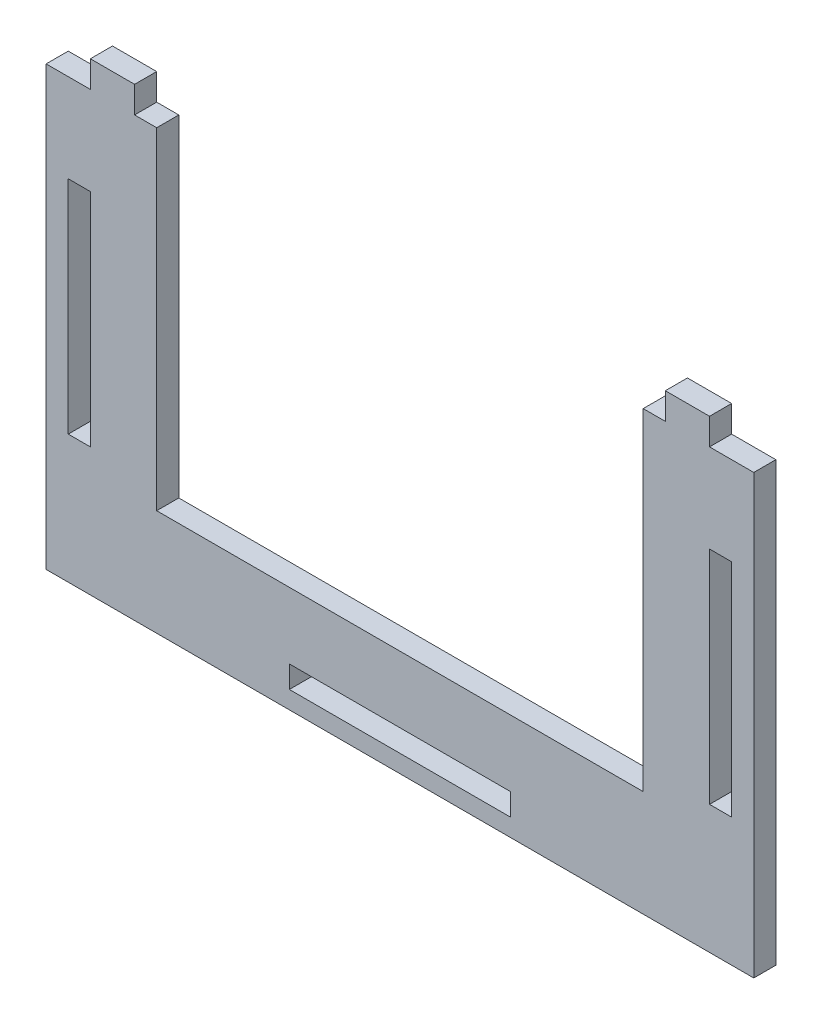
SolidWorks part; units mm, degrees
ref_plane "Front Plane" through (0, 0, 0) normal (0, 0, 1) x (1, 0, 0)
ref_plane "Top Plane" through (0, 0, 0) normal (0, 1, 0) x (1, 0, 0)
ref_plane "Right Plane" through (0, 0, 0) normal (1, 0, 0) x (0, 0, -1)
sketch "Sketch1" plane through (0, 0, 0) normal (0, 0, 1) x (1, 0, 0)
  line L0 (-44.45, 28.575) -> (-44.45, -34.29) construction
  line L1 (-50.8, 28.575) -> (-44.45, 28.575)
  line L2 (-50.8, 28.575) -> (-50.8, -34.29)
  line L3 (-50.8, -34.29) -> (50.8, -34.29)
  line L4 (50.8, 28.575) -> (50.8, -34.29)
  line L5 (44.45, 28.575) -> (44.45, -34.29) construction
  line L6 (-15.875, -28.575) -> (-50.8, -28.575) construction
  line L7 (-15.875, -28.575) -> (15.875, -28.575)
  line L8 (-15.875, -28.575) -> (-15.875, -31.75)
  line L9 (-15.875, -31.75) -> (15.875, -31.75)
  line L10 (15.875, -28.575) -> (15.875, -31.75)
  line L11 (15.875, -28.575) -> (50.8, -28.575) construction
  line L12 (34.925, 28.575) -> (38.1, 28.575)
  line L13 (0, -19.05) -> (0, 0) construction
  line L14 (-38.1, 28.575) -> (-34.925, 28.575)
  line L16 (-44.45, 28.575) -> (-44.45, 32.385)
  line L17 (-47.625, 0) -> (47.625, 0) construction
  line L18 (0, -34.29) -> (0, -31.75) construction
  line L19 (-47.625, 0) -> (-44.45, 0) construction
  line L20 (-47.625, 15.875) -> (-44.45, 15.875)
  line L21 (-47.625, 15.875) -> (-47.625, -15.875)
  line L22 (-47.625, -15.875) -> (-44.45, -15.875)
  line L23 (-44.45, 15.875) -> (-44.45, -15.875)
  line L24 (44.45, 15.875) -> (47.625, 15.875)
  line L25 (44.45, 15.875) -> (44.45, -15.875)
  line L26 (44.45, -15.875) -> (47.625, -15.875)
  line L27 (47.625, 15.875) -> (47.625, -15.875)
  line L28 (47.625, 0) -> (44.45, 0) construction
  line L29 (-34.925, 28.575) -> (-34.925, -19.05)
  line L30 (-34.925, -19.05) -> (34.925, -19.05)
  line L31 (34.925, -19.05) -> (34.925, 28.575)
  line L32 (-34.925, 28.575) -> (34.925, 28.575) construction
  line L33 (-44.45, 32.385) -> (-38.1, 32.385)
  line L34 (-38.1, 28.575) -> (-38.1, 32.385)
  line L35 (44.45, 28.575) -> (50.8, 28.575)
  line L36 (44.45, 28.575) -> (44.45, 32.385)
  line L37 (44.45, 32.385) -> (38.1, 32.385)
  line L38 (38.1, 28.575) -> (38.1, 32.385)
  line L40 (0, 28.575) -> (0, 0) construction
  line L41 (0, 0) -> (0, -28.575) construction
  dimension "D1" = 88.9
  dimension "D2" = 57.15
  dimension "D3" = 2.54
  dimension "D4" = 3.175
  dimension "D5" = 31.75
  dimension "D6" = 3.81
  dimension "D7" = 3.175
  dimension "D8" = 3.175
  dimension "D9" = 3.175
  dimension "D10" = 3.175
  dimension "D11" = 31.75
  dimension "D12" = 3.81
  dimension "D13" = 69.85
  dimension "D14" = 6.35
  dimension "D15" = 6.35
  dimension "D16" = 9.525
extrude "Boss-Extrude1" add sketch "Sketch1" along normal blind 3.175
